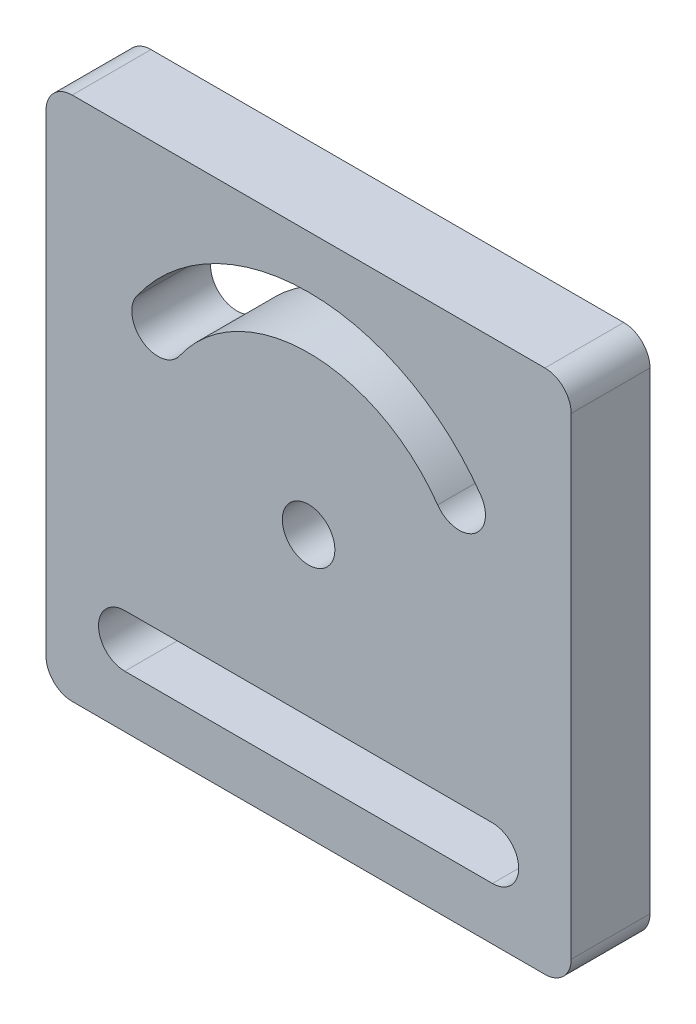
SolidWorks part; units mm, degrees
ref_plane "Front Plane" through (0, 0, 0) normal (0, 0, 1) x (1, 0, 0)
ref_plane "Top Plane" through (0, 0, 0) normal (0, 1, 0) x (1, 0, 0)
ref_plane "Right Plane" through (0, 0, 0) normal (1, 0, 0) x (0, 0, -1)
sketch "Sketch1" plane through (0, 0, 0) normal (0, 0, 1) x (1, 0, 0)
  line L0 (70, -70) -> (-70, -70) construction
  line L1 (100, -100) -> (-100, -100)
  line L2 (100, -100) -> (100, 100)
  line L3 (100, 100) -> (-100, 100)
  line L4 (-100, -100) -> (-100, 100)
  line L5 (0, 0) -> (152.3608, 0) construction
  line L6 (0, 0) -> (68.195, 47.7506) construction
  line L10 (0, 0) -> (-76.8301, 53.797) construction
  line L11 (0, -117.3982) -> (0, 0) construction
  line L12 (172.5981, -70) -> (-100, -70) construction
  line L13 (70, -80) -> (-70, -80)
  line L14 (70, -60) -> (-70, -60)
  circle A2 centre (0, 0) radius 10
  arc A3 (-57.3406, 40.1504) -> (57.3406, 40.1504) centre (0, 0) cw construction
  arc A4 (65.5322, 45.8861) -> (-65.5322, 45.8861) centre (0, 0) ccw
  arc A5 (49.1491, 34.4146) -> (-49.1491, 34.4146) centre (0, 0) ccw
  arc A6 (49.1491, 34.4146) -> (65.5322, 45.8861) centre (57.3406, 40.1504) ccw
  arc A7 (-65.5322, 45.8861) -> (-49.1491, 34.4146) centre (-57.3406, 40.1504) ccw
  arc A8 (70, -80) -> (70, -60) centre (70, -70) ccw
  arc A9 (-70, -60) -> (-70, -80) centre (-70, -70) ccw
  point P0 (0, 0)
  point P6 (6.1384, -71.02)
  point P15 (0, -70)
  point P22 (0, 70)
  dimension "D3" = 30
  dimension "D7" = 20
  dimension "D10" = 70
  dimension "D11" = 20
  dimension "D1" = 200
  dimension "D2" = 200
  dimension "D4" = 140
  dimension "D5" = 20
  dimension "D8" = 110
  dimension "D9" = 35
extrude "Boss-Extrude1" add sketch "Sketch1" along normal blind 30
fillet "Fillet1" radius 10 4 edges at (-100, -100, 15) (100, -100, 15) (100, 100, 15) (-100, 100, 15)
